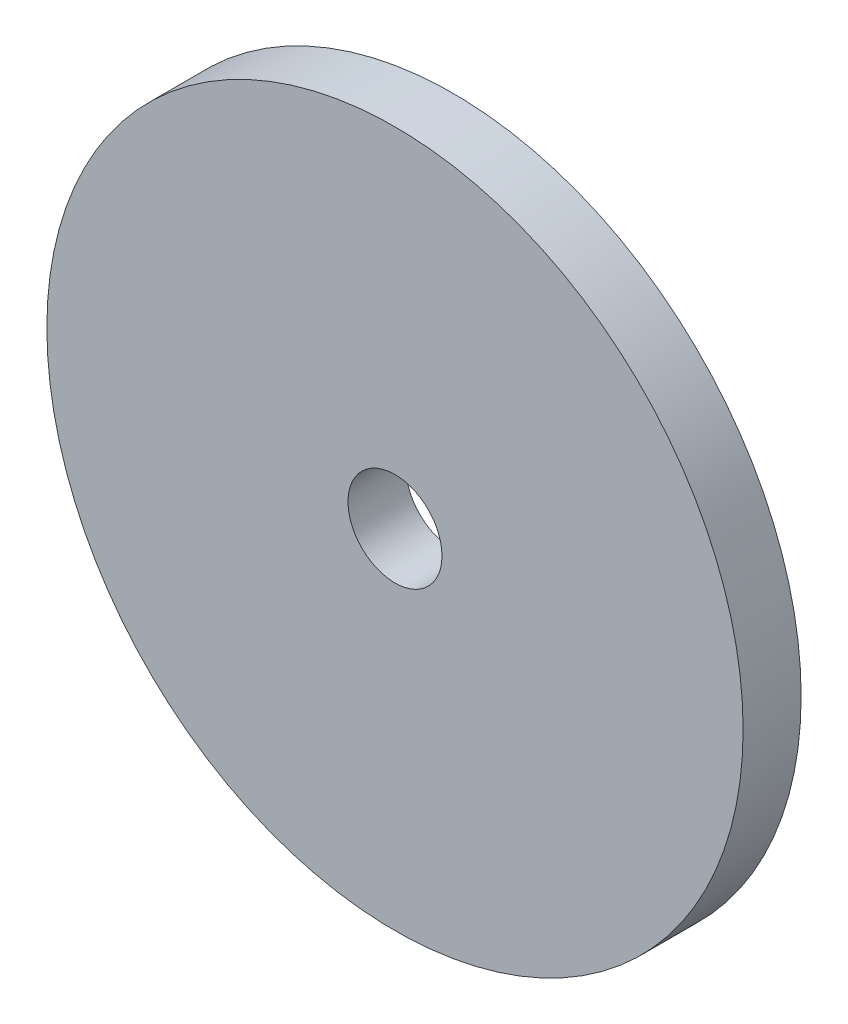
SolidWorks part; units mm, degrees
material "Balsa"
ref_plane "Front Plane" through (0, 0, 0) normal (0, 0, 1) x (1, 0, 0)
ref_plane "Top Plane" through (0, 0, 0) normal (0, 1, 0) x (1, 0, 0)
ref_plane "Right Plane" through (0, 0, 0) normal (1, 0, 0) x (0, 0, -1)
sketch "Sketch1" plane through (0, 0, 0) normal (0, 0, 1) x (1, 0, 0)
  circle A1 centre (0, 0) radius 30
  circle A2 centre (0, 0) radius 4.05
  dimension "D1" = 60
  dimension "D2" = 8.1
extrude "Boss-Extrude1" add sketch "Sketch1" along normal blind 5
